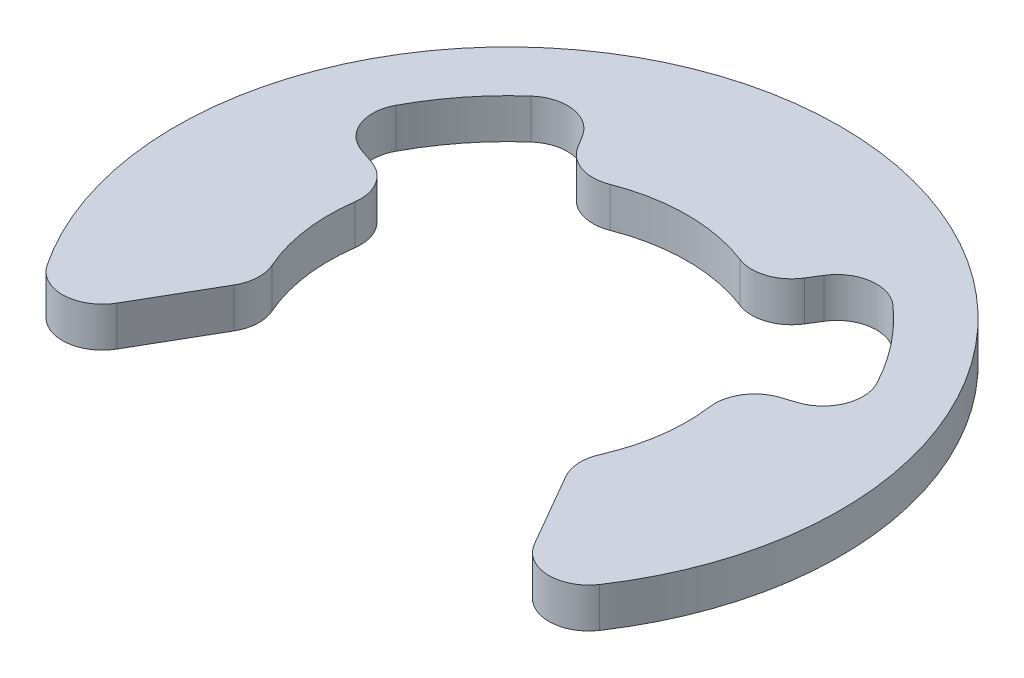
SolidWorks part; units mm, degrees
material "AISI 1045 钢，冷拔"
ref_plane "前视基准面" through (0, 0, 0) normal (0, 0, 1) x (1, 0, 0)
ref_plane "上视基准面" through (0, 0, 0) normal (0, 1, 0) x (1, 0, 0)
ref_plane "右视基准面" through (0, 0, 0) normal (1, 0, 0) x (0, 0, -1)
ref_plane "基准面1" through (0, 0.5, 0) normal (0, 1, 0) x (1, 0, 0)
sketch "草图1" plane through (0, 0.5, 0) normal (0, 1, 0) x (1, 0, 0)
  line L0 (-5.2448, -4.5842) -> (-4.1671, -2.7176)
  line L1 (-5.1362, 1.6939) -> (-5.4739, 1.8053)
  line L2 (-3.0328, 4.9015) -> (-2.8457, 4.5991)
  line L3 (2.8457, 4.5991) -> (3.0328, 4.9015)
  line L4 (5.4739, 1.8053) -> (5.1362, 1.6939)
  line L5 (4.1671, -2.7176) -> (5.2448, -4.5842)
  arc A0 (-4.1671, -2.7176) -> (-4.118, -1.8144) centre (-5.0331, -2.2176) ccw
  arc A1 (-4.118, -1.8144) -> (-4.4586, 0.6089) centre (0, 0) cw
  arc A2 (-4.4586, 0.6089) -> (-5.1362, 1.6939) centre (-5.4494, 0.7443) ccw
  arc A3 (-5.4739, 1.8053) -> (-6.0428, 3.2259) centre (-5.1607, 2.755) cw
  arc A4 (-6.0428, 3.2259) -> (-4.547, 5.1232) centre (0, 0) cw
  arc A5 (-4.547, 5.1232) -> (-3.0328, 4.9015) centre (-3.8832, 4.3753) cw
  arc A6 (-2.8457, 4.5991) -> (-1.6326, 4.1934) centre (-1.9953, 5.1253) ccw
  arc A7 (-1.6326, 4.1934) -> (1.6326, 4.1934) centre (0, 0) cw
  arc A8 (1.6326, 4.1934) -> (2.8457, 4.5991) centre (1.9953, 5.1253) ccw
  arc A9 (3.0328, 4.9015) -> (4.547, 5.1232) centre (3.8832, 4.3753) cw
  arc A10 (4.547, 5.1232) -> (6.0428, 3.2259) centre (0, 0) cw
  arc A11 (6.0428, 3.2259) -> (5.4739, 1.8053) centre (5.1607, 2.755) cw
  arc A12 (5.1362, 1.6939) -> (4.4586, 0.6089) centre (5.4494, 0.7443) ccw
  arc A13 (4.4586, 0.6089) -> (4.118, -1.8144) centre (0, 0) cw
  arc A14 (4.118, -1.8144) -> (4.1671, -2.7176) centre (5.0331, -2.2176) ccw
  arc A15 (5.2448, -4.5842) -> (6.9422, -4.6399) centre (6.1108, -4.0842) ccw
  arc A16 (6.9422, -4.6399) -> (-6.9422, -4.6399) centre (0, 0) ccw
  arc A17 (-6.9422, -4.6399) -> (-5.2448, -4.5842) centre (-6.1108, -4.0842) ccw
extrude "凸台-拉伸1" add sketch "草图1" against normal blind 1
